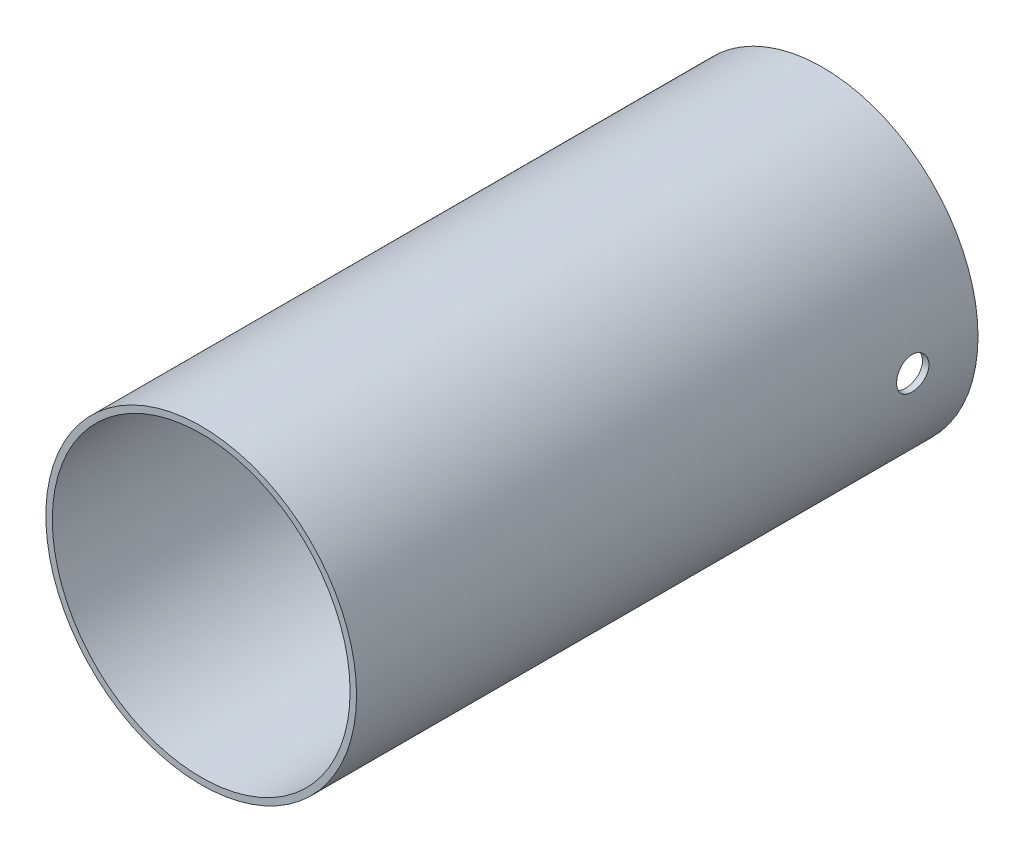
SolidWorks part; units mm, degrees
ref_plane "Front Plane" through (0, 0, 0) normal (0, 0, 1) x (1, 0, 0)
ref_plane "Top Plane" through (0, 0, 0) normal (0, 1, 0) x (1, 0, 0)
ref_plane "Right Plane" through (0, 0, 0) normal (1, 0, 0) x (0, 0, -1)
sketch "Sketch1" plane through (0, 0, 0) normal (0, 0, 1) x (1, 0, 0)
  line L0 (-38.1, 0) -> (38.1, 0) construction
  line L1 (-36.5125, 0) -> (36.5125, 0) construction
  circle A0 centre (0, 0) radius 38.1 construction
  circle A1 centre (0, 0) radius 36.5125 construction
  point P4 (0, 0)
  point P10 (0, 0)
  dimension "ID" = 73.025
  dimension "OD" = 76.2
  dimension "Wall Thickness" = 1.5875
sketch "Sketch2" plane through (0, 0, 0) normal (1, 0, 0) x (0, 0, -1)
  line L0 (152.4, 0) -> (-152.4, 0) construction
  line L2 (-152.4, -38.1) -> (152.4, -38.1) construction
  line L3 (-152.4, -38.1) -> (-152.4, 38.1) construction
  line L4 (-152.4, 38.1) -> (152.4, 38.1) construction
  line L5 (152.4, -38.1) -> (152.4, 38.1) construction
  line L6 (0, 38.1) -> (0, -38.1) construction
  line L7 (-152.4, 0) -> (152.4, 0) construction
  point P0 (-19.05, 0)
  point P3 (0, 0)
  point P4 (0, 0)
  point P6 (19.05, 0)
  dimension "D2" = 133.35
  dimension "D3" = 133.35
  dimension "Length" = 304.8
sketch "Sketch3" plane through (0, 0, 0) normal (0, 0, 1) x (1, 0, 0)
  circle A0 centre (0, 0) radius 38.1
  circle A1 centre (0, 0) radius 36.5125 construction
  circle A2 centre (0, 0) radius 36.5125
  dimension "D1" = 76.2
extrude "Boss-Extrude1" add sketch "Sketch3" along normal blind 152.4
hole_wizard "5/16 (0.3125) Diameter Hole1" positions "3DSketch1" profile "Sketch4" hole size "5/16" standard "ANSI Inch"
sketch3d "3DSketch1"
  point P0 (-34.6239, -15.8995, 39.6725)
  point P1 (-38.1, -0.0424, 15.9972)
  point P3 (-38.1, -0.0424, 15.9972)
sketch "Sketch4" plane through (-38.1, -0.0424, 15.9972) normal (0, 0, 1) x (0.0011, -1, 0)
  line L0 (0, 0) -> (0, 76.2424)
  line L1 (0, 76.2424) -> (3.9687, 76.2424)
  line L2 (3.9687, 76.2424) -> (3.9688, 0)
  line L5 (3.9688, 0) -> (0, 0)
  line L11 (0, -6.35) -> (0, 107.95) construction
  dimension "Thru Hole Dia." = 7.9375
  dimension "Thru Hole Depth" = 76.2424
equation "\"D2@Sketch2\" = \"OD@Sketch1\" * 1.75"
equation "\"D3@Sketch2\"=\"D2@Sketch2\""
equation "\"D1@Sketch3\" = \"OD@Sketch1\""
equation "\"D1@Boss-Extrude1\"=\"Length@Sketch2\""
